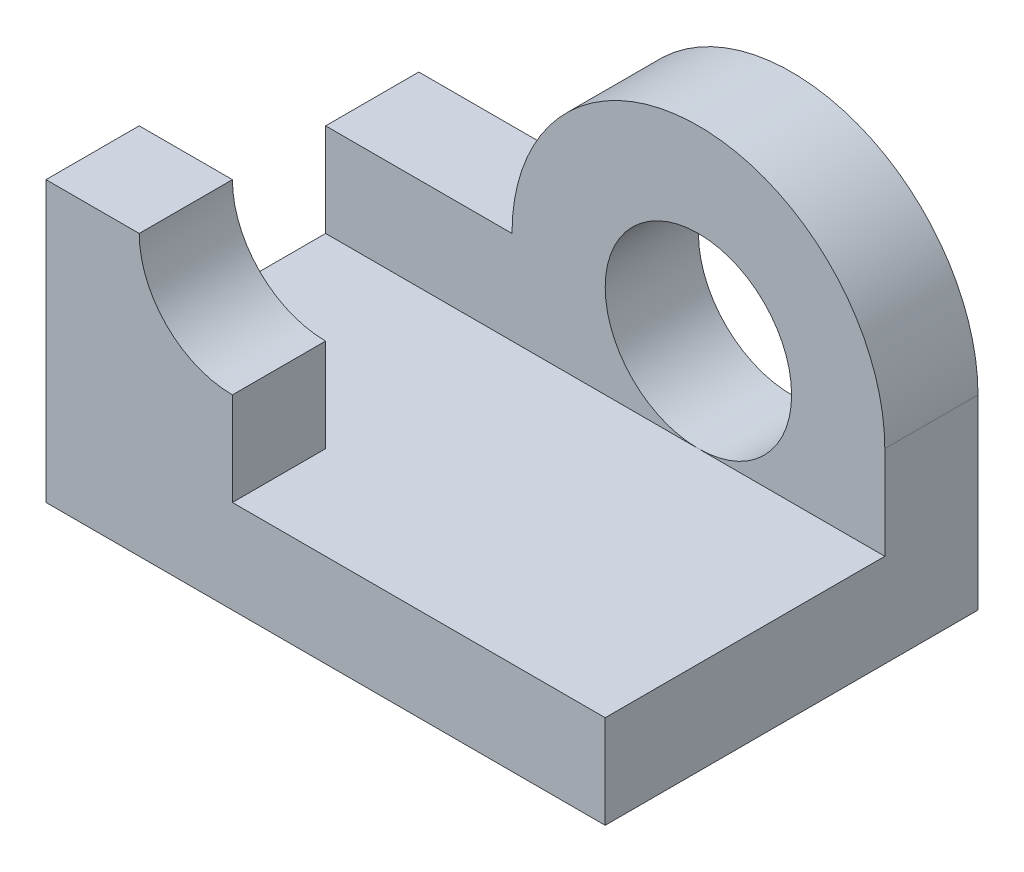
SolidWorks part; units mm, degrees
ref_plane "Front Plane" through (0, 0, 0) normal (0, 0, 1) x (1, 0, 0)
ref_plane "Top Plane" through (0, 0, 0) normal (0, 1, 0) x (1, 0, 0)
ref_plane "Right Plane" through (0, 0, 0) normal (1, 0, 0) x (0, 0, -1)
sketch "Sketch1" plane through (0, 0, 0) normal (0, 0, 1) x (1, 0, 0)
  line L1 (0, 0) -> (-60, 0)
  line L2 (0, 0) -> (0, 10)
  line L3 (0, 10) -> (-60, 10)
  line L4 (-60, 0) -> (-60, 10)
  dimension "D1" = 60
  dimension "D2" = 10
extrude "Boss-Extrude1" add sketch "Sketch1" against normal blind 40
sketch "Sketch3" plane through (0, 0, -40) normal (0, 0, -1) x (-1, 0, 0)
  line L0 (0, 10) -> (0, 20)
  line L1 (60, 10) -> (60, 20)
  line L2 (60, 20) -> (40, 20)
  line L7 (0, 10) -> (0, 0)
  line L8 (0, 0) -> (60, 0)
  line L9 (60, 0) -> (60, 10)
  line L10 (60, 10) -> (0, 10)
  line L11 (0, 10) -> (0, 0)
  line L12 (0, 0) -> (60, 0)
  line L13 (60, 0) -> (60, 10)
  arc A0 (40, 20) -> (0, 20) centre (20, 20) ccw
  dimension "D3" = 0
  dimension "D1" = 10
  dimension "D2" = 20
extrude "Boss-Extrude2" add sketch "Sketch3" against normal blind 10
sketch "Sketch4" plane through (0, 0, -40) normal (0, 0, -1) x (-1, 0, 0)
  circle A0 centre (20, 20) radius 10
  dimension "D1" = 20
extrude "Cut-Extrude1" cut sketch "Sketch4" against normal through all
sketch "Sketch5" plane through (0, 0, 0) normal (0, 0, 1) x (1, 0, 0)
  line L0 (-60, 10) -> (-60, 30)
  line L1 (-60, 30) -> (-50, 30)
  line L2 (-60, 10) -> (-40, 10)
  line L3 (-20, 10) -> (-60, 10) construction
  line L4 (-40, 10) -> (-40, 20)
  arc A0 (-50, 30) -> (-40, 20) centre (-40, 30) ccw
  dimension "D1" = 20
  dimension "D2" = 10
extrude "Boss-Extrude3" add sketch "Sketch5" against normal blind 10
